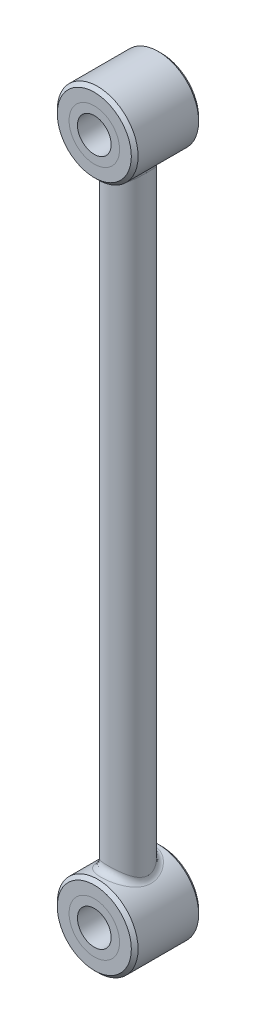
SolidWorks part; units mm, degrees
ref_plane "Front Plane" through (0, 0, 0) normal (0, 0, 1) x (1, 0, 0)
ref_plane "Top Plane" through (0, 0, 0) normal (0, 1, 0) x (1, 0, 0)
ref_plane "Right Plane" through (0, 0, 0) normal (1, 0, 0) x (0, 0, -1)
sketch "Sketch1" plane through (0, 0, 0) normal (0, 1, 0) x (1, 0, 0)
  circle A0 centre (0, 0) radius 3
  dimension "D1" = 6
extrude "Boss-Extrude1" add sketch "Sketch1" along normal mid plane 92
sketch "Sketch2" plane through (0, 0, 0) normal (0, 0, 1) x (1, 0, 0)
  circle A0 centre (0, 51) radius 6
  circle A1 centre (0, -51) radius 6
  circle A2 centre (0, 51) radius 3.75
  circle A3 centre (0, -51) radius 3.75
  dimension "D1" = 12
  dimension "D2" = 51
  dimension "D3" = 12
  dimension "D5" = 7.5
  dimension "D6" = 7.5
  dimension "D4" = 51
extrude "Boss-Extrude2" add sketch "Sketch2" along normal mid plane 10
sketch "Sketch3" plane through (0, 0, 0) normal (0, 0, 1) x (1, 0, 0)
  circle A0 centre (0, 51) radius 3.75
  circle A1 centre (0, 51) radius 2.5
  circle A2 centre (0, -51) radius 3.75
  circle A3 centre (0, -51) radius 2.5
  dimension "D1" = 7.5
  dimension "D2" = 5
  dimension "D3" = 7.5
  dimension "D4" = 5
extrude "Boss-Extrude3" add sketch "Sketch3" along normal mid plane 10 separate body
fillet "Fillet1" radius 1 2 edges at (-0.3027, -45.0076, 2.9847) (0.3027, 45.0076, 2.9847)
chamfer "Chamfer2" distance 0.5 angle 45 4 edges at (6, -51, 5) (6, -51, -5) (6, 51, -5) (6, 51, 5)
